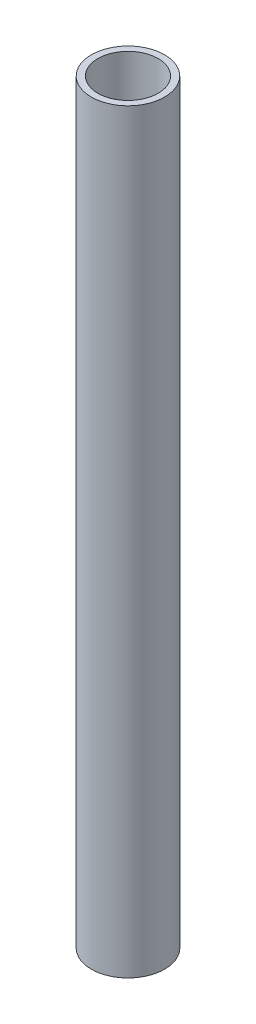
SolidWorks part; units mm, degrees
material "Thornel Mat VMA"
ref_plane "Front Plane" through (0, 0, 0) normal (0, 0, 1) x (1, 0, 0)
ref_plane "Top Plane" through (0, 0, 0) normal (0, 1, 0) x (1, 0, 0)
ref_plane "Right Plane" through (0, 0, 0) normal (1, 0, 0) x (0, 0, -1)
sketch "Sketch1" plane through (0, 0, 0) normal (0, 1, 0) x (1, 0, 0)
  circle A0 centre (0, 0) radius 7.9375
  circle A1 centre (0, 0) radius 9.652
  dimension "D1" = 15.875
  dimension "D2" = 19.304
extrude "Boss-Extrude1" add sketch "Sketch1" along normal blind 199
